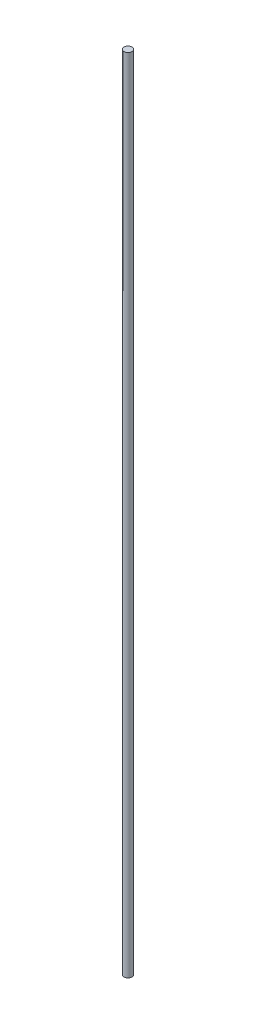
SolidWorks part; units mm, degrees
ref_plane "前视基准面" through (0, 0, 0) normal (0, 0, 1) x (1, 0, 0)
ref_plane "上视基准面" through (0, 0, 0) normal (0, 1, 0) x (1, 0, 0)
ref_plane "右视基准面" through (0, 0, 0) normal (1, 0, 0) x (0, 0, -1)
sketch "草图1" plane through (0, 0, 0) normal (0, 1, 0) x (1, 0, 0)
  circle A0 centre (0, 0) radius 2.5
  dimension "D1" = 5
extrude "凸台-拉伸1" add sketch "草图1" along normal blind 500
